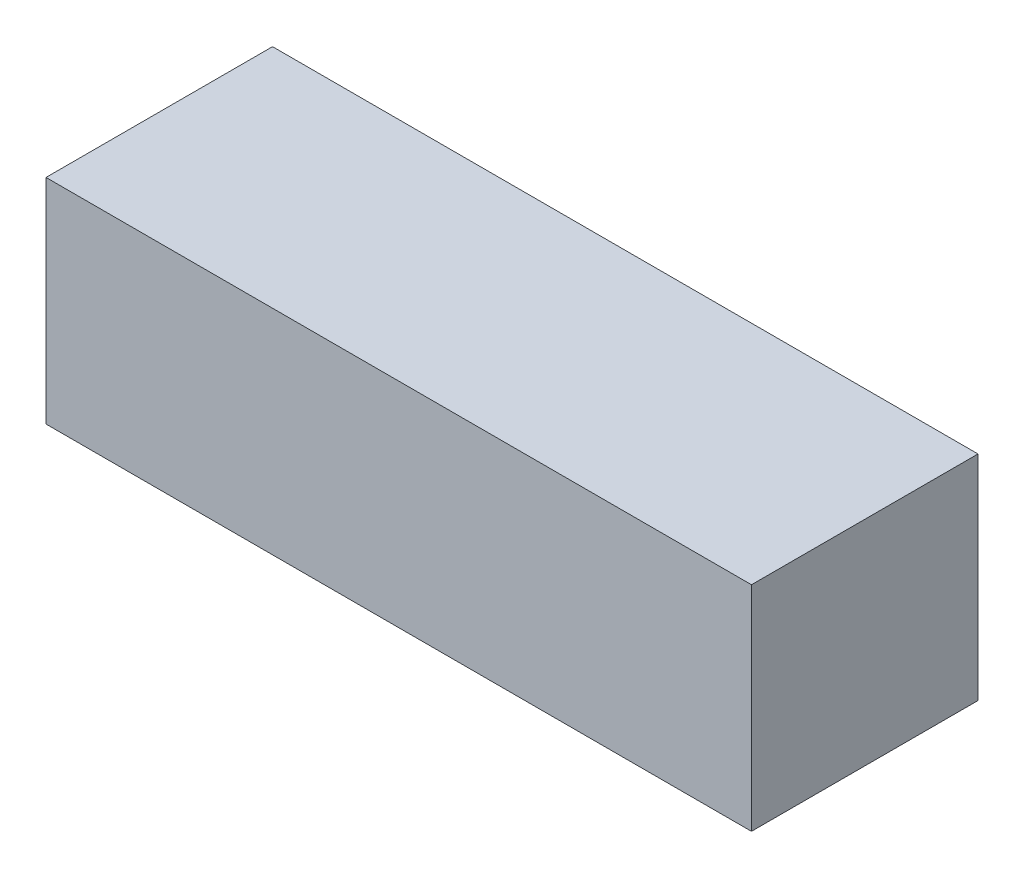
SolidWorks part; units mm, degrees
ref_plane "Front Plane" through (0, 0, 0) normal (0, 0, 1) x (1, 0, 0)
ref_plane "Top Plane" through (0, 0, 0) normal (0, 1, 0) x (1, 0, 0)
ref_plane "Right Plane" through (0, 0, 0) normal (1, 0, 0) x (0, 0, -1)
sketch "Sketch1" plane through (0, 0, 0) normal (0, 1, 0) x (1, 0, 0)
  line L1 (-54.5, 17.5) -> (54.5, 17.5)
  line L2 (-54.5, 17.5) -> (-54.5, -17.5)
  line L3 (-54.5, -17.5) -> (54.5, -17.5)
  line L4 (54.5, 17.5) -> (54.5, -17.5)
  line L5 (-54.5, 17.5) -> (54.5, -17.5) construction
  line L6 (-54.5, -17.5) -> (54.5, 17.5) construction
  point P0 (0, 0)
  dimension "D1" = 109
  dimension "D2" = 35
extrude "Boss-Extrude1" add sketch "Sketch1" along normal mid plane 33
